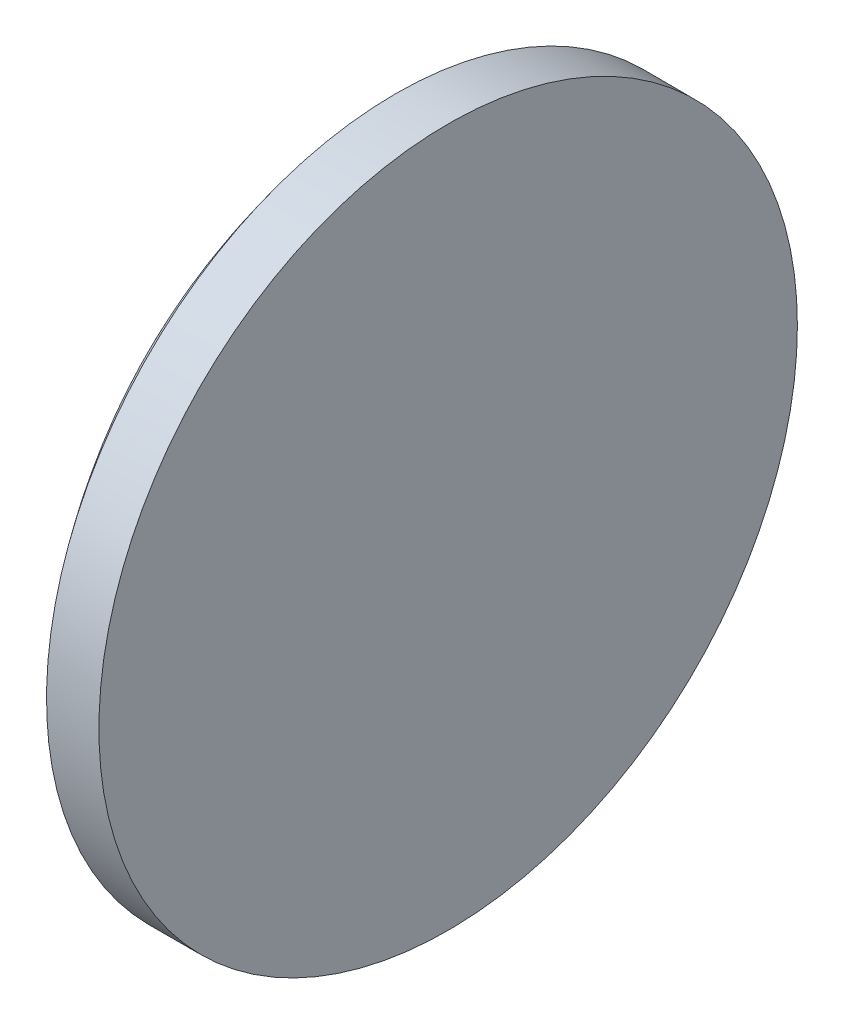
SolidWorks part; units mm, degrees
material "Glass"
ref_plane "Front Plane" through (0, 0, 0) normal (0, 0, 1) x (1, 0, 0)
ref_plane "Top Plane" through (0, 0, 0) normal (0, 1, 0) x (1, 0, 0)
ref_plane "Right Plane" through (0, 0, 0) normal (1, 0, 0) x (0, 0, -1)
sketch "Lens Profile" plane through (0, 0, 0) normal (0, 0, 1) x (1, 0, 0)
  line L0 (0, 0) -> (0, 10) construction
  line L1 (0, 0) -> (-9.6333, 0) construction
  line L2 (0, 2) -> (-0.3, 2)
  line L3 (-1, -0.5563) -> (-1, 0.5563) construction
  line L4 (-1, 0) -> (0, 0)
  line L5 (0, 0) -> (0, 2)
  spline S0 degree 3 poles (-0.3, 2) (-0.7629, 1.4061) (-1, 0.9477) (-1, 0) knots 0 0 0 0 1 1 1 1
  dimension "D1" = 0.3
  dimension "D2" = 2
  dimension "D3" = 1
revolve "Lens Revolve" add sketch "Lens Profile" angle 360 about L1
